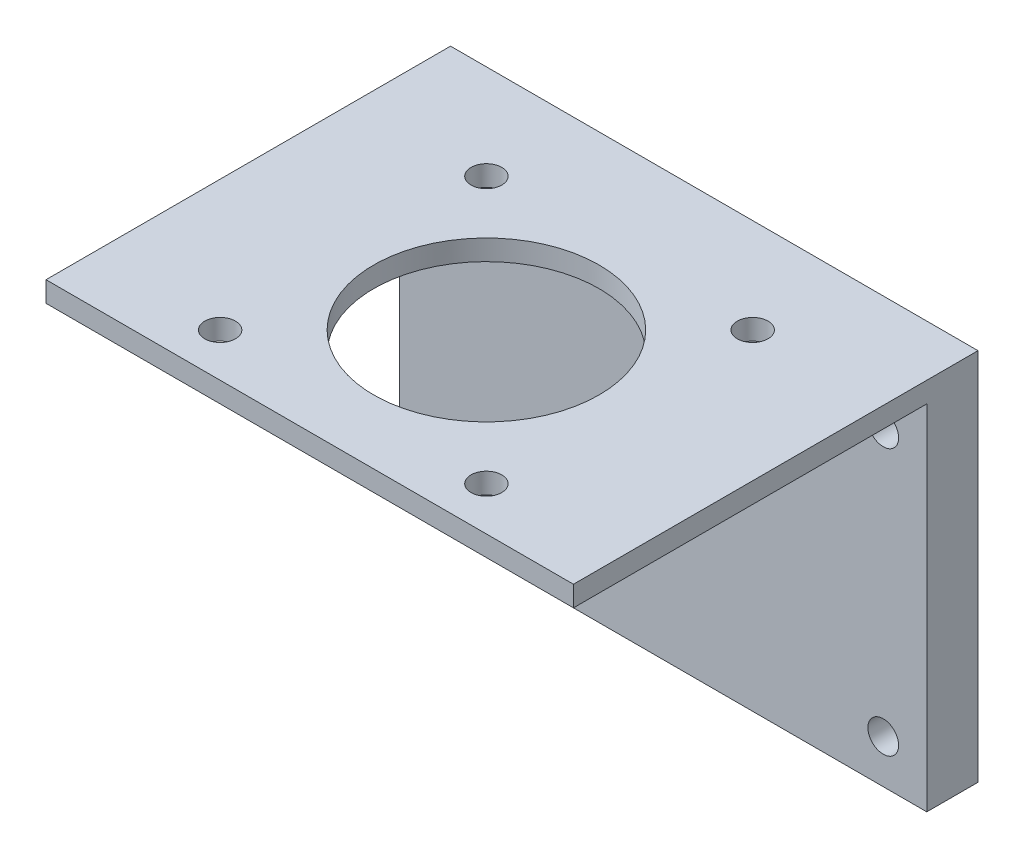
SolidWorks part; units mm, degrees
ref_plane "Plan de face" through (0, 0, 0) normal (0, 0, 1) x (1, 0, 0)
ref_plane "Plan de dessus" through (0, 0, 0) normal (0, 1, 0) x (1, 0, 0)
ref_plane "Plan de droite" through (0, 0, 0) normal (1, 0, 0) x (0, 0, -1)
sketch "Esquisse1" plane through (0, 0, 0) normal (0, 0, 1) x (1, 0, 0)
  line L1 (-14.6322, 10.8657) -> (36.8678, 10.8657)
  line L2 (-14.6322, 10.8657) -> (-14.6322, -25.6343)
  line L3 (-14.6322, -25.6343) -> (36.8678, -25.6343)
  line L4 (36.8678, 10.8657) -> (36.8678, -25.6343)
  dimension "D1" = 51.5
  dimension "D2" = 36.5
extrude "Boss.-Extru.1" add sketch "Esquisse1" along normal blind 5
sketch "Esquisse2" plane through (0, 0, 5) normal (0, 0, 1) x (1, 0, 0)
  line L0 (-14.6322, 10.8657) -> (-14.6322, -25.6343) construction
  line L1 (36.8678, 10.8657) -> (-14.6322, 10.8657) construction
  line L2 (-14.6322, -25.6343) -> (36.8678, -25.6343) construction
  line L3 (36.8678, -25.6343) -> (36.8678, 10.8657) construction
  circle A0 centre (-10.3822, 4.6157) radius 1.5
  circle A1 centre (-10.3822, -21.3843) radius 1.5
  circle A2 centre (32.6178, -21.3843) radius 1.5
  circle A3 centre (32.6178, 4.6157) radius 1.5
  dimension "D1" = 4.25
  dimension "D2" = 6.25
  dimension "D3" = 4.25
  dimension "D4" = 4.25
extrude "Enlèv. mat.-Extru.1" cut sketch "Esquisse2" against normal blind 5
sketch "Esquisse3" plane through (0, 0, 5) normal (0, 0, 1) x (1, 0, 0)
  line L0 (-14.6322, 10.8657) -> (-14.6322, 8.8657)
  line L1 (-14.6322, 10.8657) -> (-14.6322, -25.6343) construction
  line L2 (-14.6322, 8.8657) -> (36.8678, 8.8657)
  line L3 (36.8678, -25.6343) -> (36.8678, 10.8657) construction
  line L4 (36.8678, 8.8657) -> (36.8678, 10.8657)
  line L5 (36.8678, 10.8657) -> (-14.6322, 10.8657)
extrude "Boss.-Extru.3" add sketch "Esquisse3" along normal blind 34.5
sketch "Esquisse5" plane through (0, 8.8657, 0) normal (0, -1, 0) x (1, 0, 0)
  line L0 (-14.6322, 39.5) -> (-14.6322, 5) construction
  line L1 (-14.6322, 39.5) -> (36.8678, 39.5) construction
  line L2 (36.8678, 39.5) -> (36.8678, 5) construction
  line L3 (-14.6322, 5) -> (36.8678, 5) construction
  circle A0 centre (-1.8822, 35.25) radius 1.5
  circle A1 centre (24.1178, 35.25) radius 1.5
  circle A2 centre (-1.8822, 9.25) radius 1.5
  circle A3 centre (24.1178, 9.25) radius 1.5
  circle A4 centre (11.1178, 22.25) radius 11
  dimension "D1" = 12.75
  dimension "D2" = 4.25
  dimension "D3" = 12.75
  dimension "D4" = 4.25
  dimension "D5" = 25.75
  dimension "D6" = 17.25
extrude "Enlèv. mat.-Extru.3" cut sketch "Esquisse5" against normal blind 34.5
